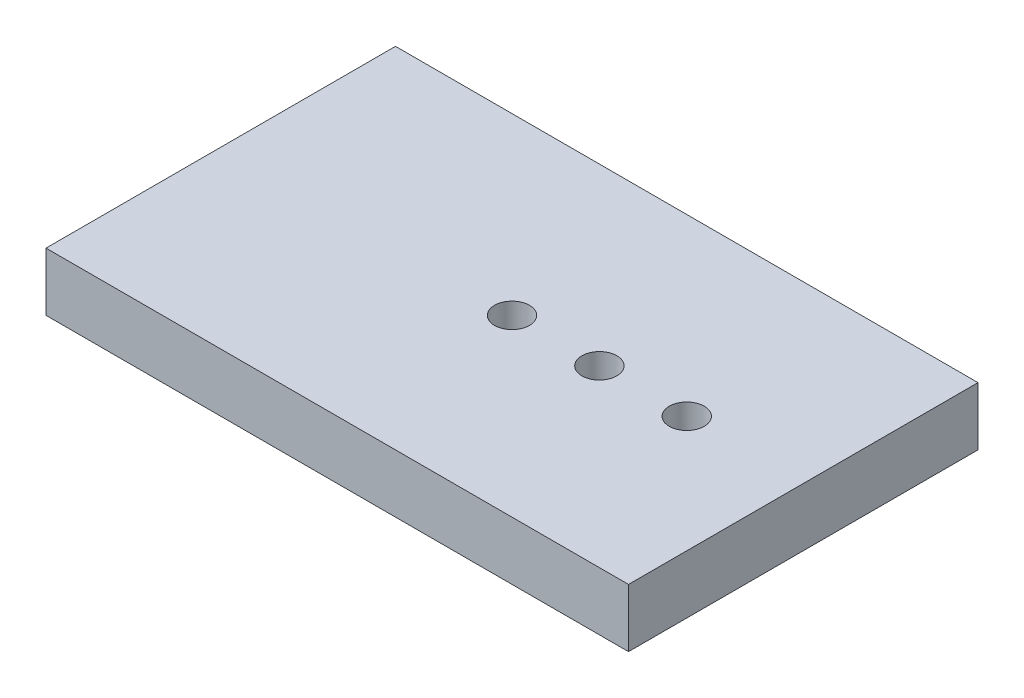
SolidWorks part; units mm, degrees
ref_plane "前视基准面" through (0, 0, 0) normal (0, 0, 1) x (1, 0, 0)
ref_plane "上视基准面" through (0, 0, 0) normal (0, 1, 0) x (1, 0, 0)
ref_plane "右视基准面" through (0, 0, 0) normal (1, 0, 0) x (0, 0, -1)
other "Configuration Table"
sketch "草图1" plane through (0, 0, 0) normal (0, 1, 0) x (1, 0, 0)
  line L1 (-50, -30) -> (50, -30)
  line L2 (-50, -30) -> (-50, 30)
  line L3 (-50, 30) -> (50, 30)
  line L4 (50, -30) -> (50, 30)
  line L5 (-50, -30) -> (50, 30) construction
  line L6 (-50, 30) -> (50, -30) construction
  point P0 (0, 0)
extrude "凸台-拉伸1" add sketch "草图1" along normal blind 10
sketch "草图2" plane through (0, 0, 0) normal (0, 1, 0) x (1, 0, 0)
  circle A0 centre (30, 0) radius 3
extrude "切除-拉伸1" cut sketch "草图2" along normal blind 20
pattern_linear "阵列(线性)1" count 3 spacing 15 along (-1, 0, 0) of "切除-拉伸1"
